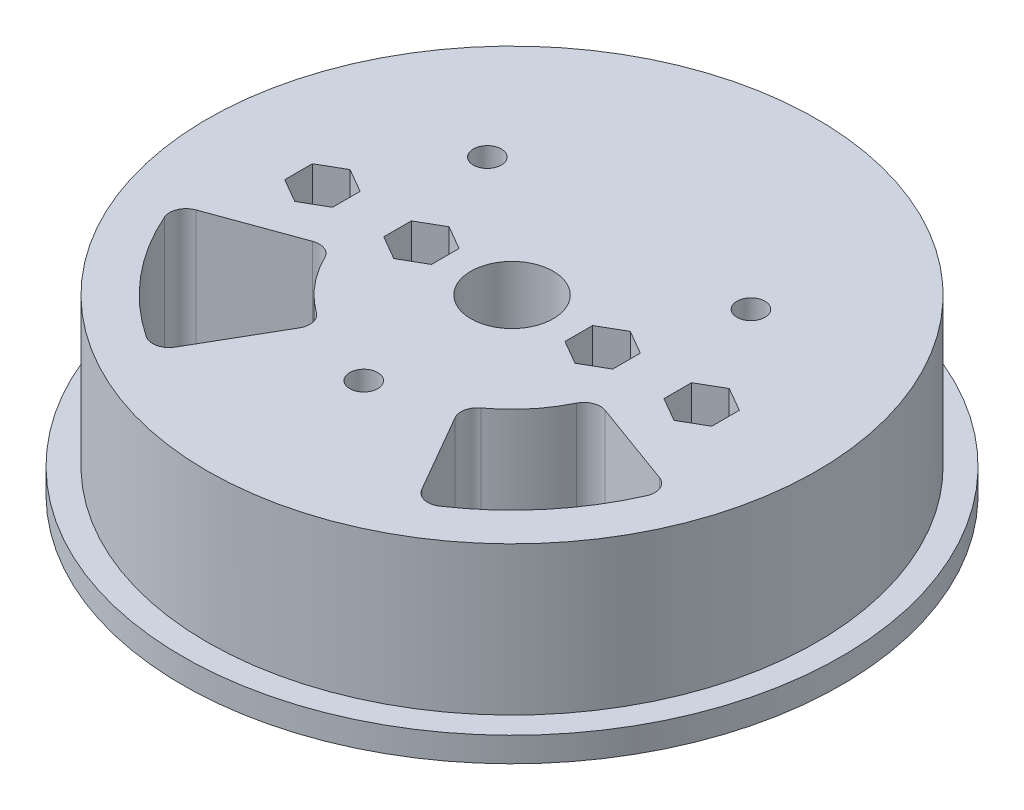
SolidWorks part; units mm, degrees
material "PLA"
ref_plane "Alzado" through (0, 0, 0) normal (0, 0, 1) x (1, 0, 0)
ref_plane "Planta" through (0, 0, 0) normal (0, 1, 0) x (1, 0, 0)
ref_plane "Vista lateral" through (0, 0, 0) normal (1, 0, 0) x (0, 0, -1)
sketch "Croquis1" plane through (0, 0, 0) normal (0, 0, 1) x (1, 0, 0)
  line L0 (0, 0) -> (40, 0)
  line L1 (40, 0) -> (40, 3)
  line L2 (40, 3) -> (37, 3)
  line L3 (37, 3) -> (37, 21)
  line L4 (37, 21) -> (0, 21)
  line L5 (0, 21) -> (0, 0)
  dimension "D1" = 37
  dimension "D2" = 40
  dimension "D3" = 3
  dimension "D4" = 18
revolve "Revolución1" add sketch "Croquis1" angle 360 about L5
sketch "Croquis2" plane through (0, 0, 0) normal (0, -1, 0) x (1, 0, 0)
  line L0 (-11.5, -19.5) -> (11.5, -19.5)
  line L1 (11.5, -19.5) -> (11.5, -23)
  line L2 (11.5, -23) -> (5, -29.5)
  line L3 (5, -29.5) -> (5, -54.5)
  line L4 (5, -54.5) -> (2.5, -54.5)
  line L5 (2.5, -54.5) -> (2.5, -29.5)
  line L6 (2.5, -29.5) -> (9, -23)
  line L7 (9, -23) -> (-9, -23)
  line L8 (-9, -23) -> (-2.5, -29.5)
  line L9 (-2.5, -29.5) -> (-2.5, -54.5)
  line L10 (-2.5, -54.5) -> (-5, -54.5)
  line L11 (-5, -54.5) -> (-5, -29.5)
  line L12 (-5, -29.5) -> (-11.5, -23)
  line L13 (-11.5, -23) -> (-11.5, -19.5)
  point P2 (0, -19.5)
  point P15 (0, -23)
  dimension "D1" = 3.5
  dimension "D2" = 2.5
  dimension "D3" = 45
  dimension "D4" = 45
  dimension "D5" = 5
  dimension "D6" = 6.5
  dimension "D7" = 19.5
  dimension "D8" = 25
extrude "Cortar-Extruir1" cut sketch "Croquis2" against normal blind 13
ref_plane "Plano1" through (0, 0, -40) normal (0, 0, 1) x (1, 0, 0)
sketch "Croquis3" plane through (0, 0, -40) normal (0, 0, 1) x (1, 0, 0)
  circle A0 centre (0, 6.5) radius 1.7
  dimension "D2" = 3.4
  dimension "D1" = 6.5
extrude "Cortar-Extruir2" cut sketch "Croquis3" along normal up to surface (17 mm away) up to face at (0, 6.5, -23)
ref_plane "Plano2" through (0, 0, -25.85) normal (0, 0, 1) x (1, 0, 0)
sketch "Croquis4" plane through (0, 0, -25.85) normal (0, 0, 1) x (1, 0, 0)
  line L0 (2.5, 13) -> (2.5, 3) construction
  line L1 (0, 9.85) -> (-2.9012, 8.175)
  line L2 (-2.9012, 8.175) -> (-2.9012, 4.825)
  line L3 (-2.9012, 4.825) -> (0, 3.15) construction
  line L4 (0, 3.15) -> (2.9012, 4.825) construction
  line L5 (2.9012, 4.825) -> (2.9012, 8.175)
  line L6 (2.9012, 8.175) -> (0, 9.85)
  line L7 (-2.9012, 4.825) -> (-2.9012, -1.825)
  line L8 (-2.9012, -1.825) -> (2.9012, -1.825)
  line L9 (2.9012, -1.825) -> (2.9012, 4.825)
  circle A0 centre (0, 6.5) radius 3.35 construction
  dimension "D2" = 6.7
  dimension "D1" = 10
extrude "Cortar-Extruir3" cut sketch "Croquis4" against normal blind 1.5 and the other way blind 1.5
sketch "Croquis5" plane through (0, 21, 0) normal (0, 1, 0) x (1, 0, 0)
  circle A0 centre (0, 0) radius 5
  dimension "D1" = 10
extrude "Cortar-Extruir4" cut sketch "Croquis5" against normal up to surface (21 mm away) up to face at (0, 0, -17.9608)
sketch "Croquis6" plane through (0, 0, 0) normal (0, -1, 0) x (1, 0, 0)
  circle A0 centre (0, 0) radius 8.2
  dimension "D1" = 16.4
extrude "Cortar-Extruir5" cut sketch "Croquis6" against normal blind 9
sketch "Croquis7" plane through (0, 0, 0) normal (0, -1, 0) x (1, 0, 0)
  line L1 (15.3, -3.5) -> (-15.3, -3.5)
  line L2 (15.3, -3.5) -> (15.3, 3.5)
  line L3 (15.3, 3.5) -> (-15.3, 3.5)
  line L4 (-15.3, -3.5) -> (-15.3, 3.5)
  line L5 (15.3, -3.5) -> (-15.3, 3.5) construction
  line L6 (15.3, 3.5) -> (-15.3, -3.5) construction
  point P0 (0, 0)
  dimension "D1" = 7
  dimension "D2" = 30.6
extrude "Cortar-Extruir6" cut sketch "Croquis7" against normal blind 4
sketch "Croquis8" plane through (0, 4, 0) normal (0, -1, 0) x (1, 0, 0)
  line L0 (-11, 0) -> (11, 0) construction
  circle A0 centre (-11, 0) radius 1.7
  circle A1 centre (11, 0) radius 1.7
  point P2 (0, 0)
  dimension "D1" = 3.4
  dimension "D2" = 22
extrude "Cortar-Extruir7" cut sketch "Croquis8" against normal up to surface (17 mm away) up to face at (0, 21, 5)
sketch "Croquis9" plane through (0, 21, 0) normal (0, 1, 0) x (1, 0, 0)
  line L0 (0, 12.1666) -> (0, -11.2589) construction
  line L1 (-11, 3.35) -> (-13.9012, 1.675)
  line L2 (-13.9012, 1.675) -> (-13.9012, -1.675)
  line L3 (-13.9012, -1.675) -> (-11, -3.35)
  line L4 (-11, -3.35) -> (-8.0988, -1.675)
  line L5 (-8.0988, -1.675) -> (-8.0988, 1.675)
  line L6 (-8.0988, 1.675) -> (-11, 3.35)
  line L7 (11, 3.35) -> (8.0988, 1.675)
  line L8 (8.0988, 1.675) -> (8.0988, -1.675)
  line L9 (8.0988, -1.675) -> (11, -3.35)
  line L10 (11, -3.35) -> (13.9012, -1.675)
  line L11 (13.9012, -1.675) -> (13.9012, 1.675)
  line L12 (13.9012, 1.675) -> (11, 3.35)
  line L13 (-23.015, 0) -> (-11, 0) construction
  line L14 (-17.0075, 0) -> (-17.0075, 7.0341) construction
  line L15 (11, 0) -> (23.015, 0) construction
  line L16 (17.0075, 0) -> (17.0075, 4.7489) construction
  line L17 (-25.9162, 1.675) -> (-23.015, 3.35)
  line L18 (-25.9162, -1.675) -> (-25.9162, 1.675)
  line L19 (-23.015, -3.35) -> (-25.9162, -1.675)
  line L20 (-20.1138, -1.675) -> (-23.015, -3.35)
  line L21 (-20.1138, 1.675) -> (-20.1138, -1.675)
  line L22 (-23.015, 3.35) -> (-20.1138, 1.675)
  line L23 (20.1138, 1.675) -> (23.015, 3.35)
  line L24 (20.1138, -1.675) -> (20.1138, 1.675)
  line L25 (23.015, -3.35) -> (20.1138, -1.675)
  line L26 (25.9162, -1.675) -> (23.015, -3.35)
  line L27 (25.9162, 1.675) -> (25.9162, -1.675)
  line L28 (23.015, 3.35) -> (25.9162, 1.675)
  circle A0 centre (-11, 0) radius 3.35 construction
  circle A1 centre (11, 0) radius 3.35 construction
  circle A2 centre (0, 0) radius 23.015 construction
  dimension "D1" = 6.7
  dimension "D2" = 46.03
extrude "Cortar-Extruir8" cut sketch "Croquis9" against normal blind 11
sketch "Croquis10" plane through (0, 0, 0) normal (0, -1, 0) x (1, 0, 0)
  line L0 (0, 0) -> (-40, 0) construction
  line L1 (0, 0) -> (37.5877, 13.6808) construction
  line L2 (0, 0) -> (20, 34.641) construction
  line L3 (9.4472, 16.3631) -> (14.9666, 25.923)
  line L4 (17.755, 6.4623) -> (28.1281, 10.2378)
  arc A0 (5, -39.6863) -> (-5, -39.6863) centre (0, 0) ccw construction
  arc A1 (15.274, 7.4636) -> (10.0025, 13.7459) centre (0, 0) ccw
  arc A2 (29.2736, 12.925) -> (17.8119, 26.5845) centre (0, 0) ccw
  arc A3 (28.1281, 10.2378) -> (29.2736, 12.925) centre (27.444, 12.1172) ccw
  arc A4 (17.755, 6.4623) -> (15.274, 7.4636) centre (17.0709, 8.3417) cw
  arc A5 (10.0025, 13.7459) -> (9.4472, 16.3631) centre (11.1793, 15.3631) cw
  arc A6 (14.9666, 25.923) -> (17.8119, 26.5845) centre (16.6987, 24.923) cw
  point P15 (30.0702, 10.9446)
  point P18 (15.9748, 5.8143)
  point P21 (8.5, 14.7224)
  point P24 (16, 27.7128)
  dimension "D3" = 17
  dimension "D4" = 32
  dimension "D5" = 2
  dimension "D1" = 200
  dimension "D2" = 40
extrude "Cortar-Extruir9" cut sketch "Croquis10" against normal up to surface (21 mm away) up to face at (23.015, 21, 0)
mirror "Simetría1" about plane through (0, 0, 0) normal (1, 0, 0) of "Cortar-Extruir9"
sketch "Croquis11" plane through (0, 0, 0) normal (0, -1, 0) x (1, 0, 0)
  line L0 (-16, -13) -> (16, -13) construction
  circle A0 centre (-16, -13) radius 1.7
  circle A1 centre (16, -13) radius 1.7
  circle A2 centre (0, 18) radius 1.7
  point P6 (0, -13)
  dimension "D3" = 3.4
  dimension "D1" = 32
  dimension "D2" = 13
  dimension "D4" = 18
extrude "Cortar-Extruir10" cut sketch "Croquis11" against normal up to surface (21 mm away) up to face at (-17.9699, 21, 15.0786)
sketch "Croquis12" plane through (0, 0, 0) normal (0, -1, 0) x (1, 0, 0)
  circle A0 centre (-16, -13) radius 2.95
  circle A1 centre (16, -13) radius 2.95
  circle A2 centre (0, 18) radius 2.95
  dimension "D1" = 5.9
extrude "Cortar-Extruir11" cut sketch "Croquis12" against normal blind 3
sketch "Sketch1" plane through (0, 0, 0) normal (0, -1, 0) x (1, 0, 0)
  line L0 (0, 0) -> (-13.2069, 7.625)
  line L1 (0, 0) -> (0, 15.25) construction
  line L2 (0, 0) -> (13.2069, 7.625)
  line L3 (0, 0) -> (13.2069, -7.625)
  line L4 (-15.25, 0) -> (15.25, 0) construction
  line L5 (0, 0) -> (-13.2069, -7.625)
  circle A0 centre (0, 0) radius 10
  circle A1 centre (0, 0) radius 15.25
  circle A2 centre (0, 0) radius 23.015
  circle A3 centre (-23.015, 0) radius 1.7055
  circle A4 centre (23.015, 0) radius 7
  circle A5 centre (-23.015, 0) radius 7
  circle M3 centre (0, 18) radius 2.95
  dimension "D1" = 20
  dimension "D2" = 30.5
  dimension "D7" = 46.03
  dimension "D8" = 14
  dimension "D9" = 14
  dimension "D3" = 30
  dimension "D4" = 30
  dimension "D5" = 30
  dimension "D6" = 30
extrude "Boss-Extrude1" add sketch "Sketch1" along normal blind 3 contours A2 A3 | A2 A5 A3 | A2 A5 A3 | A2 A3 | A2 A4 | A2 A4 | L2 A1 L0 A0 M3 | L5 A1 L3 A0
sketch "Sketch2" plane through (0, -3, 0) normal (0, -1, 0) x (-1, 0, 0)
  circle A0 centre (23.015, 0) radius 1.7
  circle A1 centre (-23.015, 0) radius 1.7
  dimension "D1" = 3.4
  dimension "D2" = 3.4
extrude "Cut-Extrude1" cut sketch "Sketch2" against normal through all
sketch "Sketch3" plane through (0, 21, 0) normal (0, 1, 0) x (1, 0, 0)
  line L0 (-25.9162, 1.675) -> (-23.015, 3.35)
  line L1 (-23.015, 3.35) -> (-20.1138, 1.675)
  line L2 (-20.1138, 1.675) -> (-20.1138, -1.675)
  line L3 (-20.1138, -1.675) -> (-23.015, -3.35)
  line L4 (-23.015, -3.35) -> (-25.9162, -1.675)
  line L5 (-25.9162, -1.675) -> (-25.9162, 1.675)
  line L6 (23.015, 3.35) -> (20.1138, 1.675)
  line L7 (20.1138, 1.675) -> (20.1138, -1.675)
  line L8 (20.1138, -1.675) -> (23.015, -3.35)
  line L9 (23.015, -3.35) -> (25.9162, -1.675)
  line L10 (25.9162, -1.675) -> (25.9162, 1.675)
  line L11 (25.9162, 1.675) -> (23.015, 3.35)
extrude "Cut-Extrude2" cut sketch "Sketch3" against normal blind 22.5
